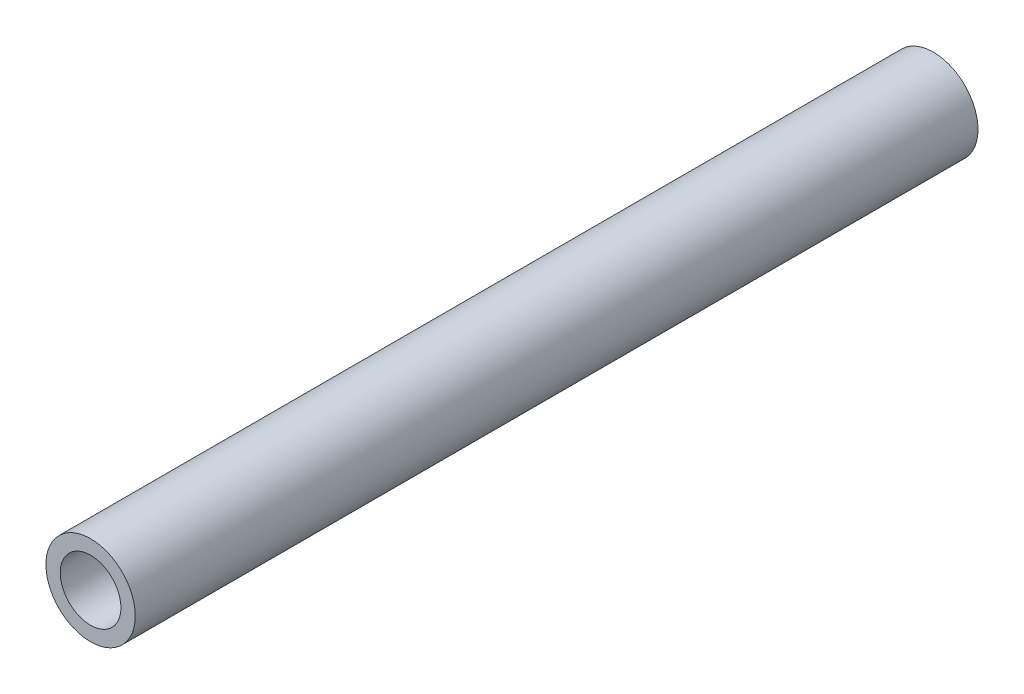
SolidWorks part; units mm, degrees
ref_plane "Front Plane" through (0, 0, 0) normal (0, 0, 1) x (1, 0, 0)
ref_plane "Top Plane" through (0, 0, 0) normal (0, 1, 0) x (1, 0, 0)
ref_plane "Right Plane" through (0, 0, 0) normal (1, 0, 0) x (0, 0, -1)
sketch "Sketch1" plane through (0, 0, 0) normal (0, 0, 1) x (1, 0, 0)
  circle A0 centre (0, 0) radius 2.65
  circle A1 centre (0, 0) radius 1.8
  dimension "D1" = 5.3
  dimension "D2" = 3.6
extrude "Boss-Extrude1" add sketch "Sketch1" along normal blind 50
